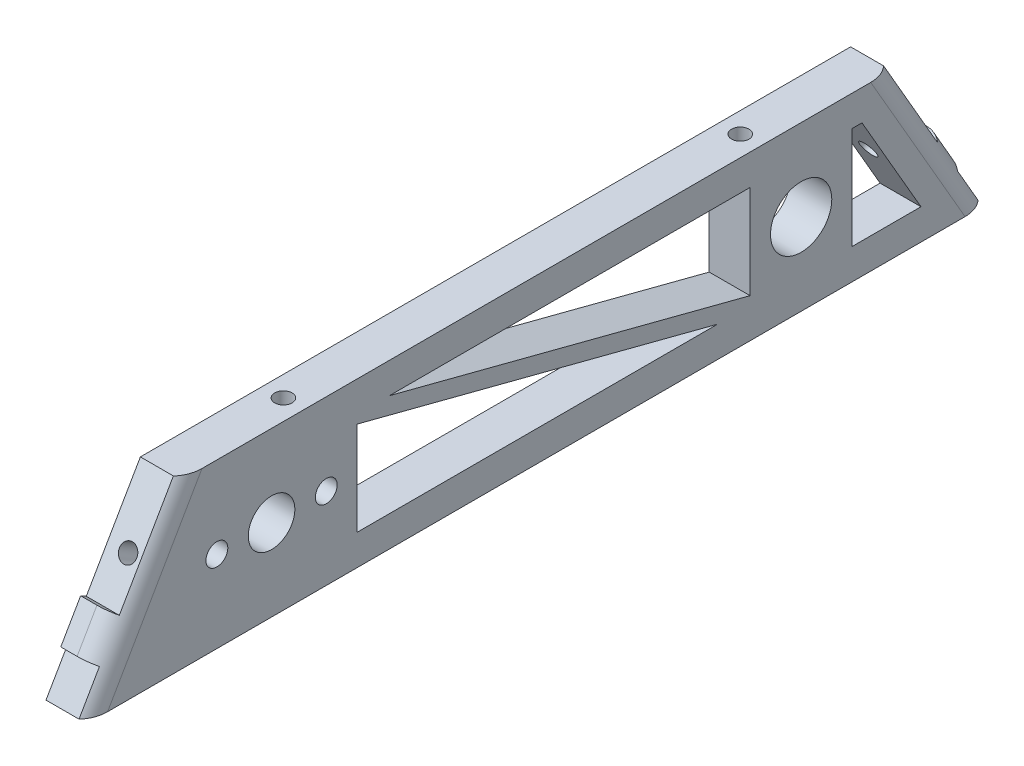
SolidWorks part; units mm, degrees
material "6061-T6 (SS)"
ref_plane "Front Plane" through (0, 0, 0) normal (0, 0, 1) x (1, 0, 0)
ref_plane "Top Plane" through (0, 0, 0) normal (0, 1, 0) x (1, 0, 0)
ref_plane "Right Plane" through (0, 0, 0) normal (1, 0, 0) x (0, 0, -1)
sketch "Sketch1" plane through (0, 0, 0) normal (1, 0, 0) x (0, 0, -1)
  line L0 (0, 0) -> (-14.6647, 25.4)
  line L1 (0, 0) -> (-139.7, 0)
  line L3 (-14.6647, 25.4) -> (-125.0353, 25.4)
  line L5 (-139.7, 0) -> (-125.0353, 25.4)
  circle A0 centre (-110.998, 12.7) radius 3.6195
  circle A1 centre (-28.702, 12.7) radius 4.7625
  circle A2 centre (-102.498, 12.7) radius 1.7
  circle A3 centre (-119.498, 12.7) radius 1.7
  dimension "D3" = 7.239
  dimension "D5" = 9.525
  dimension "D9" = 3.4
  dimension "D2" = 25.4
  dimension "D4" = 12.7
  dimension "D6" = 139.7
  dimension "D7" = 28.702
  dimension "D8" = 12.7
  dimension "D10" = 8.5
  dimension "D11" = 8.5
  dimension "D13" = 60
  dimension "D14" = 60
  dimension "D15" = 28.702
extrude "Boss-Extrude1" add sketch "Sketch1" along normal blind 6.35
hole_wizard "Tap Drill for #6-32 Tap4" positions "Sketch7" profile "Sketch6" hole size "#6-32" standard "ANSI Inch"
sketch "Sketch7" plane through (0, 25.4, 0) normal (0, 1, 0) x (1, 0, 0)
  line L2 (0, -14.6647) -> (0, -125.0353) construction
  line L4 (6.35, -14.6647) -> (6.35, -125.0353) construction
  line L7 (6.35, -14.6647) -> (0, -14.6647) construction
  line L8 (6.35, -125.0353) -> (0, -125.0353) construction
  point P0 (3.175, -105.9853)
  point P2 (3.175, -34.9847)
  point P16 (3.175, -34.9847)
  point P18 (3.175, -105.9853)
  point P22 (3.175, -105.9853)
  dimension "D1" = 19.05
  dimension "D2" = 20.32
  dimension "D3" = 3.175
  dimension "D4" = 3.175
sketch "Sketch6" plane through (3.175, 25.4, 105.9853) normal (1, 0, 0) x (0, 0, 1)
  line L0 (0, 0) -> (0, 10.9727)
  line L1 (0, 10.9727) -> (1.3525, 10.16)
  line L2 (1.3525, 10.16) -> (1.3525, 0)
  line L5 (1.3525, 0) -> (0, 0)
  line L10 (0, 10.9727) -> (-1.3526, 10.16) construction
  line L11 (0, -6.35) -> (0, 107.95) construction
  dimension "Hole Dia." = 2.7051
  dimension "Hole Depth" = 10.16
  dimension "Drill Angle" = 118
hole_wizard "Tap Drill for #6-32 Tap3" positions "Sketch9" profile "Sketch8" hole size "#6-32" standard "ANSI Inch"
sketch "Sketch9" plane through (0, 0, 0) normal (0, -1, 0) x (-1, 0, 0)
  line L1 (0, -139.7) -> (0, 0) construction
  line L3 (-6.35, 0) -> (0, 0) construction
  line L4 (-6.35, -139.7) -> (0, -139.7) construction
  point P0 (-3.175, -105.41)
  point P2 (-3.175, -22.86)
  dimension "D1" = 22.86
  dimension "D2" = 3.175
  dimension "D3" = 34.29
  dimension "D4" = 3.175
sketch "Sketch8" plane through (3.175, 0, 105.41) normal (1, 0, 0) x (0, 0, -1)
  line L0 (0, 0) -> (0, 10.9727)
  line L1 (0, 10.9727) -> (1.3525, 10.16)
  line L2 (1.3525, 10.16) -> (1.3525, 0)
  line L5 (1.3525, 0) -> (0, 0)
  line L10 (0, 10.9727) -> (-1.3526, 10.16) construction
  line L11 (0, -6.35) -> (0, 107.95) construction
  dimension "Hole Dia." = 2.7051
  dimension "Hole Depth" = 10.16
  dimension "Drill Angle" = 118
sketch "Sketch11" plane through (0, 60.4919, 104.775) normal (0, 0.5, 0.866) x (1, 0, 0)
  line L0 (0, -40.5206) -> (0, -69.85) construction
  line L1 (0, -57.3278) -> (6.35, -57.3278)
  line L2 (0, -57.3278) -> (0, -63.5)
  line L3 (0, -63.5) -> (6.35, -63.5)
  line L4 (6.35, -57.3278) -> (6.35, -63.5)
  line L5 (6.35, -40.5206) -> (6.35, -69.85) construction
  line L6 (6.35, -69.85) -> (0, -69.85) construction
  dimension "D1" = 6.1722
  dimension "D2" = 6.35
extrude "Boss-Extrude2" add sketch "Sketch11" along normal blind 1.016
sketch "Sketch12" plane through (0, 0, 0) normal (0, 0.5, -0.866) x (-1, 0, 0)
  line L0 (-6.35, 0) -> (-6.35, 29.3294) construction
  line L1 (-6.35, 12.5222) -> (0, 12.5222)
  line L2 (-6.35, 12.5222) -> (-6.35, 6.35)
  line L3 (-6.35, 6.35) -> (0, 6.35)
  line L4 (0, 12.5222) -> (0, 6.35)
  line L5 (0, 0) -> (0, 29.3294) construction
  line L6 (-6.35, 0) -> (0, 0) construction
  dimension "D1" = 6.1722
  dimension "D2" = 6.35
extrude "Boss-Extrude3" add sketch "Sketch12" along normal blind 1.016
hole_wizard "Tap Drill for #6-32 Tap1" positions "Sketch14" profile "Sketch13" hole size "#6-32" standard "ANSI Inch"
sketch "Sketch14" plane through (0, 60.4919, 104.775) normal (0, 0.5, 0.866) x (1, 0, 0)
  line L0 (6.35, -40.5206) -> (6.35, -57.3278) construction
  line L1 (6.35, -40.5206) -> (0, -40.5206) construction
  point P0 (3.175, -50.6806)
  dimension "D1" = 3.175
  dimension "D2" = 10.16
sketch "Sketch13" plane through (3.175, 16.6012, 130.1153) normal (1, 0, 0) x (0, -0.866, 0.5)
  line L0 (0, 0) -> (0, 8.4327)
  line L1 (0, 8.4327) -> (1.3525, 7.62)
  line L2 (1.3525, 7.62) -> (1.3525, 0)
  line L5 (1.3525, 0) -> (0, 0)
  line L10 (0, 8.4327) -> (-1.3526, 7.62) construction
  line L11 (0, -6.35) -> (0, 107.95) construction
  dimension "Hole Dia." = 2.7051
  dimension "Hole Depth" = 7.62
  dimension "Drill Angle" = 118
hole_wizard "Tap Drill for #6-32 Tap2" positions "Sketch16" profile "Sketch15" hole size "#6-32" standard "ANSI Inch"
sketch "Sketch16" plane through (0, 0, 0) normal (0, 0.5, -0.866) x (-1, 0, 0)
  line L0 (0, 12.5222) -> (0, 29.3294) construction
  line L1 (-6.35, 29.3294) -> (0, 29.3294) construction
  point P0 (-3.175, 19.1694)
  dimension "D1" = 3.175
  dimension "D2" = 10.16
sketch "Sketch15" plane through (3.175, 16.6012, 9.5847) normal (1, 0, 0) x (0, 0.866, 0.5)
  line L0 (0, 0) -> (0, 8.4327)
  line L1 (0, 8.4327) -> (1.3525, 7.62)
  line L2 (1.3525, 7.62) -> (1.3525, 0)
  line L5 (1.3525, 0) -> (0, 0)
  line L10 (0, 8.4327) -> (-1.3525, 7.62) construction
  line L11 (0, -6.35) -> (0, 107.95) construction
  dimension "Hole Dia." = 2.7051
  dimension "Hole Depth" = 7.62
  dimension "Drill Angle" = 118
sketch "Sketch19" plane through (0, 0, 0) normal (-1, 0, 0) x (0, 0, 1)
  line L0 (14.6647, 25.4) -> (125.0353, 25.4) construction
  line L1 (36.6395, 20.6375) -> (97.7355, 20.6375)
  line L2 (36.6395, 20.6375) -> (36.6395, 4.7625)
  line L3 (36.6395, 4.7625) -> (97.7355, 4.7625)
  line L4 (97.7355, 20.6375) -> (97.7355, 4.7625)
  line L5 (139.7, 0) -> (0, 0) construction
  line L6 (36.6395, 4.7625) -> (97.7355, 20.6375) construction
  line L7 (41.6895, 4.7625) -> (97.7355, 19.3253)
  line L8 (36.6395, 6.0747) -> (92.6855, 20.6375)
  line L9 (36.3201, 5.9917) -> (97.4161, 21.8667) construction
  line L10 (36.9589, 3.5333) -> (98.0549, 19.4083) construction
  line L11 (10.082, 4.7625) -> (19.2474, 20.6375)
  line L12 (20.7645, 20.6375) -> (20.7645, 4.7625)
  line L13 (20.7645, 4.7625) -> (10.082, 4.7625)
  line L14 (6.2611, 10.8445) -> (14.6647, 25.4) construction
  line L15 (20.7645, 20.6375) -> (19.2474, 20.6375)
  circle A0 centre (28.702, 12.7) radius 4.7625 construction
  circle A1 centre (102.498, 12.7) radius 1.7 construction
  dimension "D1" = 4.7625
  dimension "D2" = 4.7625
  dimension "D3" = 7.9375
  dimension "D4" = 4.7625
  dimension "D7" = 6.35
  dimension "D8" = 7.9375
  dimension "D9" = 4.7625
  dimension "D5" = 1.27
  dimension "D6" = 1.27
extrude "Cut-Extrude1" cut sketch "Sketch19" against normal through all contours L2 L8 L1 | L7 L3 L4 | L12 L15 L11 L13
fillet "Fillet1" radius 3.81 1 edges at (6.35, 8.6799, 135.8618)
fillet "Fillet2" radius 3.81 1 edges at (6.35, 8.6799, 3.8382)
equation "\"D8@Sketch1\"=\"D4@Sketch1\""
equation "\"D11@Sketch1\"=\"D10@Sketch1\""
